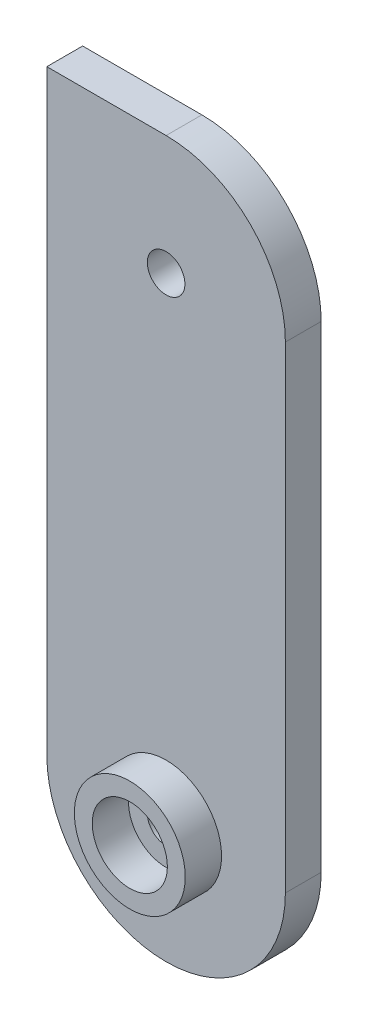
SolidWorks part; units mm, degrees
ref_plane "Front Plane" through (0, 0, 0) normal (0, 0, 1) x (1, 0, 0)
ref_plane "Top Plane" through (0, 0, 0) normal (0, 1, 0) x (1, 0, 0)
ref_plane "Right Plane" through (0, 0, 0) normal (1, 0, 0) x (0, 0, -1)
sketch "Sketch1" plane through (0, 0, 0) normal (0, 0, 1) x (1, 0, 0)
  line L0 (-21.25, 26.8088) -> (-21.25, 76.8088) construction
  line L1 (-31.25, 66.8088) -> (-31.25, 26.8088)
  line L2 (-11.25, 66.8088) -> (-11.25, 26.8088)
  line L3 (-21.25, 26.8088) -> (-21.25, 45.8088) construction
  line L4 (-23.5787, 43.5602) -> (-25.25, 26.8088)
  line L5 (-19.0787, 43.5602) -> (-17.25, 26.8088)
  line L6 (-24.5782, 43.6145) -> (-26.2497, 26.8614)
  line L7 (-18.0792, 43.6196) -> (-16.2503, 26.8663)
  line L10 (-11.25, 56.8088) -> (-11.25, 76.8088)
  line L11 (-11.25, 76.8088) -> (-31.25, 76.8088)
  line L12 (-31.25, 56.8088) -> (-31.25, 76.8088)
  line L13 (-11.25, 56.8088) -> (-31.25, 76.8088) construction
  line L14 (-11.25, 76.8088) -> (-31.25, 56.8088) construction
  arc A0 (-31.25, 26.8088) -> (-11.25, 26.8088) centre (-21.25, 26.8088) ccw
  arc A1 (-11.25, 66.8088) -> (-21.25, 76.8088) centre (-21.25, 66.8088) ccw
  arc A2 (-25.25, 26.8088) -> (-17.25, 26.8088) centre (-21.25, 26.8088) ccw
  arc A3 (-19.0787, 43.5602) -> (-23.5787, 43.5602) centre (-21.3287, 43.5602) ccw
  arc A4 (-18.0792, 43.6196) -> (-24.5782, 43.6145) centre (-21.3287, 43.5602) ccw
  arc A5 (-26.2497, 26.8614) -> (-16.2503, 26.8663) centre (-21.25, 26.8088) ccw
  dimension "D1" = 20
  dimension "D3" = 20
  dimension "D4" = 8
  dimension "D6" = 4.5
  dimension "D2" = 50
  dimension "D5" = 19
  dimension "D7" = 1
extrude "Boss-Extrude1" add sketch "Sketch1" along normal blind 3
sketch "Sketch2" plane through (0, 0, 3) normal (0, 0, 1) x (1, 0, 0)
  circle A0 centre (-21.25, 26.8088) radius 3.15
  circle A1 centre (-21.25, 26.8088) radius 4.65
  dimension "D1" = 6.3
  dimension "D2" = 1.5
extrude "Boss-Extrude2" add sketch "Sketch2" along normal up to surface (3.0444 mm away) contours A1 A0
sketch "Sketch3" plane through (0, 0, 0) normal (0, 0, -1) x (-1, 0, 0)
  circle A0 centre (21.25, 26.8088) radius 1.575
  dimension "D1" = 3.15
extrude "Cut-Extrude1" cut sketch "Sketch3" against normal up to surface (6.0444 mm away) contours A0 up to face at (-18.1, 26.8088, 6.0444)
sketch "Sketch4" plane through (0, 0, 0) normal (0, 0, -1) x (-1, 0, 0)
  circle A0 centre (21.25, 66.8088) radius 1.575
  dimension "D1" = 3.15
extrude "Cut-Extrude2" cut sketch "Sketch4" against normal blind 12
